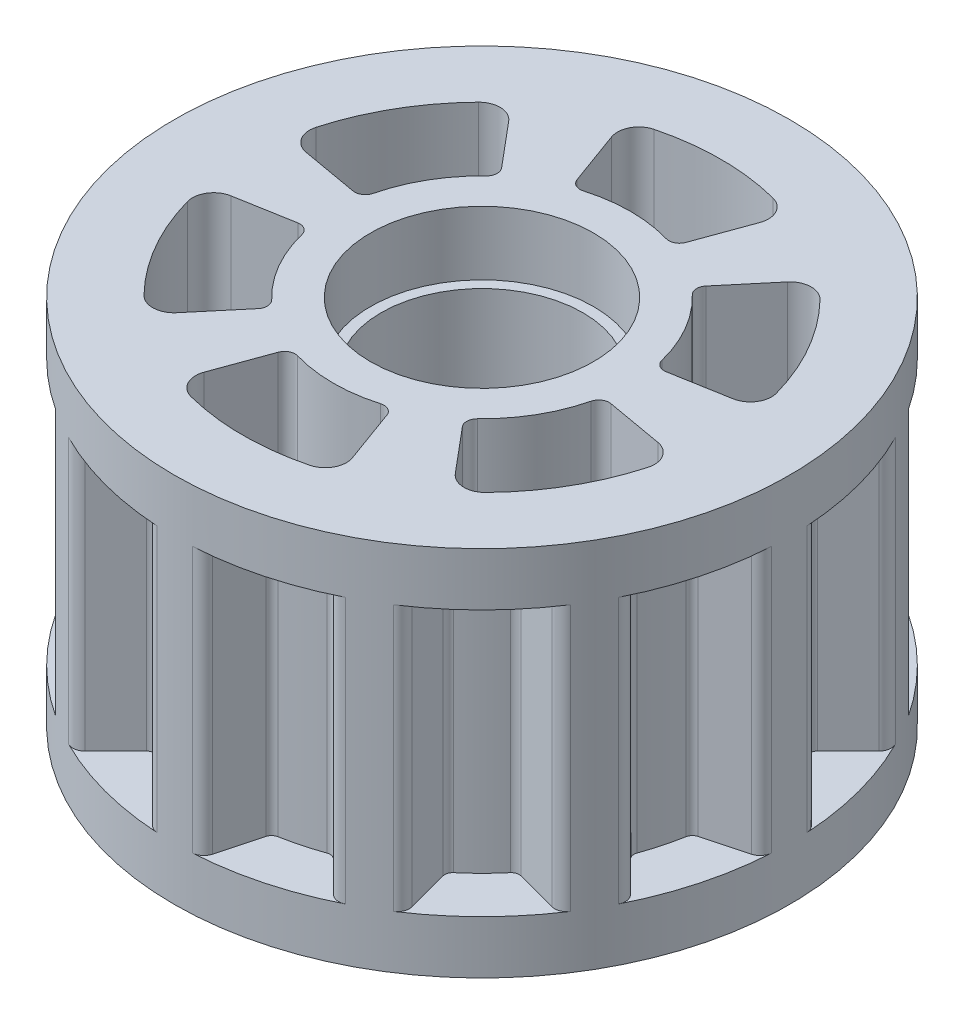
SolidWorks part; units mm, degrees
ref_plane "前视基准面" through (0, 0, 0) normal (0, 0, 1) x (1, 0, 0)
ref_plane "上视基准面" through (0, 0, 0) normal (0, 1, 0) x (1, 0, 0)
ref_plane "右视基准面" through (0, 0, 0) normal (1, 0, 0) x (0, 0, -1)
sketch "草图1" plane through (0, 0, 0) normal (0, 1, 0) x (1, 0, 0)
  line L0 (-64.3719, 0) -> (45.7906, 0) construction
  line L1 (0, 88.5907) -> (0, -93.1341) construction
  circle A0 centre (0, 0) radius 57.955
extrude "凸台-拉伸1" add sketch "草图1" along normal blind 10
ref_plane "基准面1" through (0, 10, 0) normal (0, 1, 0) x (1, 0, 0)
sketch "草图2" plane through (0, 10, 0) normal (0, 1, 0) x (1, 0, 0)
  line L0 (-37.5581, 0) -> (-8.544, 0) construction
  line L1 (0, 40.5842) -> (0, -22.7841) construction
  line L3 (4.9938, 57.7394) -> (7.5493, 48.2399) construction
  line L5 (5.4185, 56.1606) -> (7.5493, 48.2399)
  line L6 (-5.4185, 56.1606) -> (-7.5493, 48.2399)
  line L7 (23.3877, 51.3457) -> (17.5821, 45.5516)
  line L8 (32.7729, 45.9272) -> (30.6578, 38.0023)
  line L9 (45.9272, 32.7729) -> (38.0023, 30.6578)
  line L10 (51.3457, 23.3877) -> (45.5516, 17.5821)
  line L11 (56.1606, 5.4185) -> (48.2399, 7.5493)
  line L12 (56.1606, -5.4185) -> (48.2399, -7.5493)
  line L13 (51.3457, -23.3877) -> (45.5516, -17.5821)
  line L14 (45.9272, -32.7729) -> (38.0023, -30.6578)
  line L15 (32.7729, -45.9272) -> (30.6578, -38.0023)
  line L16 (23.3877, -51.3457) -> (17.5821, -45.5516)
  line L17 (5.4185, -56.1606) -> (7.5493, -48.2399)
  line L18 (-5.4185, -56.1606) -> (-7.5493, -48.2399)
  line L19 (-23.3877, -51.3457) -> (-17.5821, -45.5516)
  line L20 (-32.7729, -45.9272) -> (-30.6578, -38.0023)
  line L21 (-45.9272, -32.7729) -> (-38.0023, -30.6578)
  line L22 (-51.3457, -23.3877) -> (-45.5516, -17.5821)
  line L23 (-56.1606, -5.4185) -> (-48.2399, -7.5493)
  line L24 (-56.1606, 5.4185) -> (-48.2399, 7.5493)
  line L25 (-51.3457, 23.3877) -> (-45.5516, 17.5821)
  line L26 (-45.9272, 32.7729) -> (-38.0023, 30.6578)
  line L27 (-32.7729, 45.9272) -> (-30.6578, 38.0023)
  line L28 (-23.3877, 51.3457) -> (-17.5821, 45.5516)
  arc A0 (3.3296, 57.8593) -> (-3.3296, 57.8593) centre (0, 0) ccw
  arc A1 (5.4185, 56.1606) -> (3.3296, 57.8593) centre (3.1975, 55.5631) ccw
  arc A2 (12.4117, 46.321) -> (8.7249, 47.1546) centre (0, 0) ccw
  arc A3 (8.7249, 47.1546) -> (7.5493, 48.2399) centre (8.9978, 48.6296) cw
  arc A4 (-5.4185, 56.1606) -> (-3.3296, 57.8593) centre (-3.1975, 55.5631) cw
  arc A5 (-8.7249, 47.1546) -> (-7.5493, 48.2399) centre (-8.9978, 48.6296) ccw
  arc A6 (-12.4117, 46.321) -> (-8.7249, 47.1546) centre (0, 0) cw
  arc A7 (23.3877, 51.3457) -> (26.0461, 51.7724) centre (25.0124, 49.7178) cw
  arc A8 (16.0213, 45.1995) -> (17.5821, 45.5516) centre (16.5225, 46.6134) ccw
  arc A9 (12.4117, 46.321) -> (16.0213, 45.1995) centre (0, 0) cw
  arc A10 (31.8132, 48.4428) -> (26.0461, 51.7724) centre (0, 0) ccw
  arc A11 (32.7729, 45.9272) -> (31.8132, 48.4428) centre (30.5507, 46.5203) ccw
  arc A12 (31.1333, 36.4747) -> (30.6578, 38.0023) centre (32.1071, 37.6156) cw
  arc A13 (33.9093, 33.9093) -> (31.1333, 36.4747) centre (0, 0) ccw
  arc A14 (45.9272, 32.7729) -> (48.4428, 31.8132) centre (46.5203, 30.5507) cw
  arc A15 (36.4747, 31.1333) -> (38.0023, 30.6578) centre (37.6156, 32.1071) ccw
  arc A16 (33.9093, 33.9093) -> (36.4747, 31.1333) centre (0, 0) cw
  arc A17 (51.7724, 26.0461) -> (48.4428, 31.8132) centre (0, 0) ccw
  arc A18 (51.3457, 23.3877) -> (51.7724, 26.0461) centre (49.7178, 25.0124) ccw
  arc A19 (45.1995, 16.0213) -> (45.5516, 17.5821) centre (46.6134, 16.5225) cw
  arc A20 (46.321, 12.4117) -> (45.1995, 16.0213) centre (0, 0) ccw
  arc A21 (56.1606, 5.4185) -> (57.8593, 3.3296) centre (55.5631, 3.1975) cw
  arc A22 (47.1546, 8.7249) -> (48.2399, 7.5493) centre (48.6296, 8.9978) ccw
  arc A23 (46.321, 12.4117) -> (47.1546, 8.7249) centre (0, 0) cw
  arc A24 (57.8593, -3.3296) -> (57.8593, 3.3296) centre (0, 0) ccw
  arc A25 (56.1606, -5.4185) -> (57.8593, -3.3296) centre (55.5631, -3.1975) ccw
  arc A26 (47.1546, -8.7249) -> (48.2399, -7.5493) centre (48.6296, -8.9978) cw
  arc A27 (46.321, -12.4117) -> (47.1546, -8.7249) centre (0, 0) ccw
  arc A28 (51.3457, -23.3877) -> (51.7724, -26.0461) centre (49.7178, -25.0124) cw
  arc A29 (45.1995, -16.0213) -> (45.5516, -17.5821) centre (46.6134, -16.5225) ccw
  arc A30 (46.321, -12.4117) -> (45.1995, -16.0213) centre (0, 0) cw
  arc A31 (48.4428, -31.8132) -> (51.7724, -26.0461) centre (0, 0) ccw
  arc A32 (45.9272, -32.7729) -> (48.4428, -31.8132) centre (46.5203, -30.5507) ccw
  arc A33 (36.4747, -31.1333) -> (38.0023, -30.6578) centre (37.6156, -32.1071) cw
  arc A34 (33.9093, -33.9093) -> (36.4747, -31.1333) centre (0, 0) ccw
  arc A35 (32.7729, -45.9272) -> (31.8132, -48.4428) centre (30.5507, -46.5203) cw
  arc A36 (31.1333, -36.4747) -> (30.6578, -38.0023) centre (32.1071, -37.6156) ccw
  arc A37 (33.9093, -33.9093) -> (31.1333, -36.4747) centre (0, 0) cw
  arc A38 (26.0461, -51.7724) -> (31.8132, -48.4428) centre (0, 0) ccw
  arc A39 (23.3877, -51.3457) -> (26.0461, -51.7724) centre (25.0124, -49.7178) ccw
  arc A40 (16.0213, -45.1995) -> (17.5821, -45.5516) centre (16.5225, -46.6134) cw
  arc A41 (12.4117, -46.321) -> (16.0213, -45.1995) centre (0, 0) ccw
  arc A42 (5.4185, -56.1606) -> (3.3296, -57.8593) centre (3.1975, -55.5631) cw
  arc A43 (8.7249, -47.1546) -> (7.5493, -48.2399) centre (8.9978, -48.6296) ccw
  arc A44 (12.4117, -46.321) -> (8.7249, -47.1546) centre (0, 0) cw
  arc A45 (-3.3296, -57.8593) -> (3.3296, -57.8593) centre (0, 0) ccw
  arc A46 (-5.4185, -56.1606) -> (-3.3296, -57.8593) centre (-3.1975, -55.5631) ccw
  arc A47 (-8.7249, -47.1546) -> (-7.5493, -48.2399) centre (-8.9978, -48.6296) cw
  arc A48 (-12.4117, -46.321) -> (-8.7249, -47.1546) centre (0, 0) ccw
  arc A49 (-23.3877, -51.3457) -> (-26.0461, -51.7724) centre (-25.0124, -49.7178) cw
  arc A50 (-16.0213, -45.1995) -> (-17.5821, -45.5516) centre (-16.5225, -46.6134) ccw
  arc A51 (-12.4117, -46.321) -> (-16.0213, -45.1995) centre (0, 0) cw
  arc A52 (-31.8132, -48.4428) -> (-26.0461, -51.7724) centre (0, 0) ccw
  arc A53 (-32.7729, -45.9272) -> (-31.8132, -48.4428) centre (-30.5507, -46.5203) ccw
  arc A54 (-31.1333, -36.4747) -> (-30.6578, -38.0023) centre (-32.1071, -37.6156) cw
  arc A55 (-33.9093, -33.9093) -> (-31.1333, -36.4747) centre (0, 0) ccw
  arc A56 (-45.9272, -32.7729) -> (-48.4428, -31.8132) centre (-46.5203, -30.5507) cw
  arc A57 (-36.4747, -31.1333) -> (-38.0023, -30.6578) centre (-37.6156, -32.1071) ccw
  arc A58 (-33.9093, -33.9093) -> (-36.4747, -31.1333) centre (0, 0) cw
  arc A59 (-51.7724, -26.0461) -> (-48.4428, -31.8132) centre (0, 0) ccw
  arc A60 (-51.3457, -23.3877) -> (-51.7724, -26.0461) centre (-49.7178, -25.0124) ccw
  arc A61 (-45.1995, -16.0213) -> (-45.5516, -17.5821) centre (-46.6134, -16.5225) cw
  arc A62 (-46.321, -12.4117) -> (-45.1995, -16.0213) centre (0, 0) ccw
  arc A63 (-56.1606, -5.4185) -> (-57.8593, -3.3296) centre (-55.5631, -3.1975) cw
  arc A64 (-47.1546, -8.7249) -> (-48.2399, -7.5493) centre (-48.6296, -8.9978) ccw
  arc A65 (-46.321, -12.4117) -> (-47.1546, -8.7249) centre (0, 0) cw
  arc A66 (-57.8593, 3.3296) -> (-57.8593, -3.3296) centre (0, 0) ccw
  arc A67 (-56.1606, 5.4185) -> (-57.8593, 3.3296) centre (-55.5631, 3.1975) ccw
  arc A68 (-47.1546, 8.7249) -> (-48.2399, 7.5493) centre (-48.6296, 8.9978) cw
  arc A69 (-46.321, 12.4117) -> (-47.1546, 8.7249) centre (0, 0) ccw
  arc A70 (-51.3457, 23.3877) -> (-51.7724, 26.0461) centre (-49.7178, 25.0124) cw
  arc A71 (-45.1995, 16.0213) -> (-45.5516, 17.5821) centre (-46.6134, 16.5225) ccw
  arc A72 (-46.321, 12.4117) -> (-45.1995, 16.0213) centre (0, 0) cw
  arc A73 (-48.4428, 31.8132) -> (-51.7724, 26.0461) centre (0, 0) ccw
  arc A74 (-45.9272, 32.7729) -> (-48.4428, 31.8132) centre (-46.5203, 30.5507) ccw
  arc A75 (-36.4747, 31.1333) -> (-38.0023, 30.6578) centre (-37.6156, 32.1071) cw
  arc A76 (-33.9093, 33.9093) -> (-36.4747, 31.1333) centre (0, 0) ccw
  arc A77 (-32.7729, 45.9272) -> (-31.8132, 48.4428) centre (-30.5507, 46.5203) cw
  arc A78 (-31.1333, 36.4747) -> (-30.6578, 38.0023) centre (-32.1071, 37.6156) ccw
  arc A79 (-33.9093, 33.9093) -> (-31.1333, 36.4747) centre (0, 0) cw
  arc A80 (-26.0461, 51.7724) -> (-31.8132, 48.4428) centre (0, 0) ccw
  arc A81 (-23.3877, 51.3457) -> (-26.0461, 51.7724) centre (-25.0124, 49.7178) ccw
  arc A82 (-16.0213, 45.1995) -> (-17.5821, 45.5516) centre (-16.5225, 46.6134) cw
  arc A83 (-12.4117, 46.321) -> (-16.0213, 45.1995) centre (0, 0) ccw
  point P9 (4.9938, 57.7394)
  point P12 (7.7976, 47.3168)
  point P13 (12.4117, 46.321)
  point P21 (7.7976, 47.3168)
  point P185 (0, 0)
  dimension "D4" = 2.3
  dimension "D5" = 1.5
  dimension "D6" = 12
extrude "凸台-拉伸2" add sketch "草图2" along normal blind 50
ref_plane "基准面2" through (0, 60, 0) normal (0, 1, 0) x (1, 0, 0)
sketch "草图4" plane through (0, 60, 0) normal (0, 1, 0) x (1, 0, 0)
  circle A0 centre (0, 0) radius 57.955
extrude "凸台-拉伸3" add sketch "草图4" along normal blind 10
sketch "草图5" plane through (0, 0, 0) normal (0, 1, 0) x (1, 0, 0)
  circle A0 centre (0, 0) radius 21
extrude "切除-拉伸1" cut sketch "草图5" along normal blind 12
ref_plane "基准面3" through (0, 12, 0) normal (0, -1, 0) x (-1, 0, 0)
sketch "草图6" plane through (0, 12, 0) normal (0, -1, 0) x (-1, 0, 0)
  circle A0 centre (0, 0) radius 19
extrude "切除-拉伸2" cut sketch "草图6" against normal blind 46
ref_plane "基准面4" through (0, 58, 0) normal (0, -1, 0) x (-1, 0, 0)
sketch "草图7" plane through (0, 58, 0) normal (0, -1, 0) x (-1, 0, 0)
  circle A0 centre (0, 0) radius 21
extrude "切除-拉伸3" cut sketch "草图7" against normal through all
sketch "草图8" plane through (0, 0, 0) normal (0, 1, 0) x (1, 0, 0)
  line L0 (-35.9442, 0) -> (34.791, 0) construction
  line L1 (0, 40.636) -> (0, -32.9825) construction
  line L2 (0, 0) -> (27.3616, 75.1754) construction
  line L3 (10.2378, 28.1281) -> (13.9559, 38.3436)
  line L4 (-10.2378, 28.1281) -> (-13.9559, 38.3436)
  line L5 (29.4785, 5.1979) -> (40.1845, 7.0856)
  line L6 (19.2407, 22.9302) -> (26.2286, 31.258)
  line L7 (19.2407, -22.9302) -> (26.2286, -31.258)
  line L8 (29.4785, -5.1979) -> (40.1845, -7.0856)
  line L9 (-10.2378, -28.1281) -> (-13.9559, -38.3436)
  line L10 (10.2378, -28.1281) -> (13.9559, -38.3436)
  line L11 (-29.4785, -5.1979) -> (-40.1845, -7.0856)
  line L12 (-19.2407, -22.9302) -> (-26.2286, -31.258)
  line L13 (-19.2407, 22.9302) -> (-26.2286, 31.258)
  line L14 (-29.4785, 5.1979) -> (-40.1845, 7.0856)
  arc A0 (11.192, 43.586) -> (13.9559, 38.3436) centre (10.1972, 39.7117) cw
  arc A1 (7.8012, 26.8913) -> (10.2378, 28.1281) centre (8.3584, 28.8121) ccw
  arc A2 (7.8012, 26.8913) -> (-7.8012, 26.8913) centre (0, 0) ccw
  arc A3 (11.192, 43.586) -> (-11.192, 43.586) centre (0, 0) ccw
  arc A4 (-7.8012, 26.8913) -> (-10.2378, 28.1281) centre (-8.3584, 28.8121) cw
  arc A5 (-11.192, 43.586) -> (-13.9559, 38.3436) centre (-10.1972, 39.7117) ccw
  arc A6 (43.3426, 12.1004) -> (40.1845, 7.0856) centre (39.4899, 11.0248) cw
  arc A7 (27.1891, 6.6896) -> (29.4785, 5.1979) centre (29.1312, 7.1675) ccw
  arc A8 (27.1891, 6.6896) -> (19.388, 20.2017) centre (0, 0) ccw
  arc A9 (43.3426, 12.1004) -> (32.1506, 31.4856) centre (0, 0) ccw
  arc A10 (19.388, 20.2017) -> (19.2407, 22.9302) centre (20.7728, 21.6446) cw
  arc A11 (32.1506, 31.4856) -> (26.2286, 31.258) centre (29.2927, 28.6868) ccw
  arc A12 (32.1506, -31.4856) -> (26.2286, -31.258) centre (29.2927, -28.6868) cw
  arc A13 (19.388, -20.2017) -> (19.2407, -22.9302) centre (20.7728, -21.6446) ccw
  arc A14 (19.388, -20.2017) -> (27.1891, -6.6896) centre (0, 0) ccw
  arc A15 (32.1506, -31.4856) -> (43.3426, -12.1004) centre (0, 0) ccw
  arc A16 (27.1891, -6.6896) -> (29.4785, -5.1979) centre (29.1312, -7.1675) cw
  arc A17 (43.3426, -12.1004) -> (40.1845, -7.0856) centre (39.4899, -11.0248) ccw
  arc A18 (-11.192, -43.586) -> (-13.9559, -38.3436) centre (-10.1972, -39.7117) cw
  arc A19 (-7.8012, -26.8913) -> (-10.2378, -28.1281) centre (-8.3584, -28.8121) ccw
  arc A20 (-7.8012, -26.8913) -> (7.8012, -26.8913) centre (0, 0) ccw
  arc A21 (-11.192, -43.586) -> (11.192, -43.586) centre (0, 0) ccw
  arc A22 (7.8012, -26.8913) -> (10.2378, -28.1281) centre (8.3584, -28.8121) cw
  arc A23 (11.192, -43.586) -> (13.9559, -38.3436) centre (10.1972, -39.7117) ccw
  arc A24 (-43.3426, -12.1004) -> (-40.1845, -7.0856) centre (-39.4899, -11.0248) cw
  arc A25 (-27.1891, -6.6896) -> (-29.4785, -5.1979) centre (-29.1312, -7.1675) ccw
  arc A26 (-27.1891, -6.6896) -> (-19.388, -20.2017) centre (0, 0) ccw
  arc A27 (-43.3426, -12.1004) -> (-32.1506, -31.4856) centre (0, 0) ccw
  arc A28 (-19.388, -20.2017) -> (-19.2407, -22.9302) centre (-20.7728, -21.6446) cw
  arc A29 (-32.1506, -31.4856) -> (-26.2286, -31.258) centre (-29.2927, -28.6868) ccw
  arc A30 (-32.1506, 31.4856) -> (-26.2286, 31.258) centre (-29.2927, 28.6868) cw
  arc A31 (-19.388, 20.2017) -> (-19.2407, 22.9302) centre (-20.7728, 21.6446) ccw
  arc A32 (-19.388, 20.2017) -> (-27.1891, 6.6896) centre (0, 0) ccw
  arc A33 (-32.1506, 31.4856) -> (-43.3426, 12.1004) centre (0, 0) ccw
  arc A34 (-27.1891, 6.6896) -> (-29.4785, 5.1979) centre (-29.1312, 7.1675) cw
  arc A35 (-43.3426, 12.1004) -> (-40.1845, 7.0856) centre (-39.4899, 11.0248) ccw
  point P9 (15.3909, 42.2862)
  point P10 (9.5766, 26.3114)
  point P13 (15.3909, 42.2862)
  point P18 (9.5766, 26.3114)
  point P85 (0, 0)
  dimension "D2" = 4
  dimension "D3" = 2
  dimension "D1" = 20
  dimension "D4" = 6
extrude "切除-拉伸4" cut sketch "草图8" along normal through all
